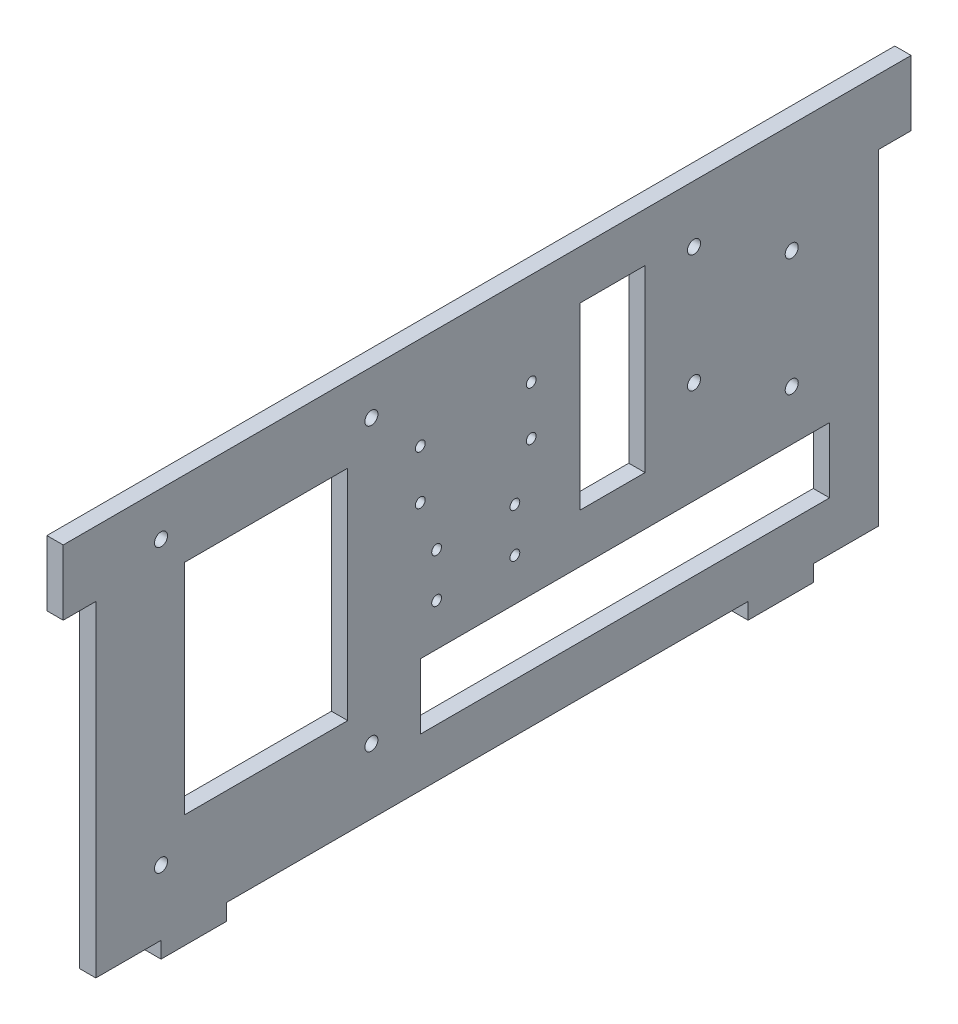
SolidWorks part; units mm, degrees
material "Perspex (TM) GS Acrylic Cast Sheet"
ref_plane "Ebene vorne" through (0, 0, 0) normal (0, 0, 1) x (1, 0, 0)
ref_plane "Ebene oben" through (0, 0, 0) normal (0, 1, 0) x (1, 0, 0)
ref_plane "Ebene rechts" through (0, 0, 0) normal (1, 0, 0) x (0, 0, -1)
sketch "Skizze2" plane through (0, 0, 0) normal (1, 0, 0) x (0, 0, -1)
  line L1 (-120, 60) -> (120, 60)
  line L2 (-120, 60) -> (-120, -60)
  line L3 (-120, -60) -> (120, -60)
  line L4 (120, 60) -> (120, -60)
  line L5 (-120, 60) -> (120, -60) construction
  line L6 (-120, -60) -> (120, 60) construction
  line L7 (-120, 60) -> (-130, 60)
  line L8 (-120, 60) -> (-120, 40)
  line L9 (-120, 40) -> (-130, 40)
  line L10 (-130, 60) -> (-130, 40)
  line L11 (-120, 60) -> (-130, 40) construction
  line L12 (-120, 40) -> (-130, 60) construction
  line L13 (120, 60) -> (130, 60)
  line L14 (120, 60) -> (120, 40)
  line L15 (120, 40) -> (130, 40)
  line L16 (130, 60) -> (130, 40)
  line L17 (120, 60) -> (130, 40) construction
  line L18 (120, 40) -> (130, 60) construction
  line L19 (100, -60) -> (80, -60)
  line L20 (100, -60) -> (100, -65)
  line L21 (100, -65) -> (80, -65)
  line L22 (80, -60) -> (80, -65)
  line L23 (-80, -60) -> (-100, -60)
  line L24 (-80, -60) -> (-80, -65)
  line L25 (-80, -65) -> (-100, -65)
  line L26 (-100, -60) -> (-100, -65)
  point P0 (0, 0)
  point P9 (-125, 50)
  point P13 (125, 50)
  dimension "D1" = 240
  dimension "D2" = 120
  dimension "D3" = 10
  dimension "D4" = 20
  dimension "D5" = 20
  dimension "D6" = 20
  dimension "D7" = 5
  dimension "D8" = 20
extrude "Aufsatz-Linear austragen1" add sketch "Skizze2" along normal blind 5
sketch "Skizze3" plane through (0, 0, 0) normal (-1, 0, 0) x (0, 0, 1)
  line L0 (80, -60) -> (-80, -60) construction
  line L1 (35.5, 46.5) -> (100, 46.5) construction
  line L2 (35.5, 46.5) -> (35.5, -40) construction
  line L3 (35.5, -40) -> (100, -40) construction
  line L4 (100, 46.5) -> (100, -40) construction
  line L5 (35.5, 46.5) -> (100, -40) construction
  line L6 (35.5, -40) -> (100, 46.5) construction
  line L7 (3.5, 24) -> (3.5, -5.25) construction
  line L8 (120, 40) -> (120, -60) construction
  line L9 (-13.5, 16.5) -> (20.5, 16.5) construction
  line L10 (-13.5, 16.5) -> (-13.5, 31.5) construction
  line L11 (-13.5, 31.5) -> (20.5, 31.5) construction
  line L12 (20.5, 16.5) -> (20.5, 31.5) construction
  line L13 (-13.5, 16.5) -> (20.5, 31.5) construction
  line L14 (-13.5, 31.5) -> (20.5, 16.5) construction
  line L15 (-8.5, -12) -> (15.5, -12) construction
  line L16 (-8.5, -12) -> (-8.5, 1.5) construction
  line L17 (-8.5, 1.5) -> (15.5, 1.5) construction
  line L18 (15.5, -12) -> (15.5, 1.5) construction
  line L19 (-8.5, -12) -> (15.5, 1.5) construction
  line L20 (-8.5, 1.5) -> (15.5, -12) construction
  circle A0 centre (35.5, 46.5) radius 2
  circle A1 centre (100, 46.5) radius 2
  circle A2 centre (100, -40) radius 2
  circle A3 centre (35.5, -40) radius 2
  circle A4 centre (20.5, 31.5) radius 1.5
  circle A5 centre (-13.5, 31.5) radius 1.5
  circle A6 centre (-13.5, 16.5) radius 1.5
  circle A7 centre (20.5, 16.5) radius 1.5
  circle A8 centre (15.5, 1.5) radius 1.5
  circle A9 centre (15.5, -12) radius 1.5
  circle A10 centre (-8.5, 1.5) radius 1.5
  circle A11 centre (-8.5, -12) radius 1.5
  point P0 (67.75, 3.25)
  point P13 (3.5, 24)
  point P22 (20.5, 24)
  point P23 (3.5, -5.25)
  dimension "D1" = 4
  dimension "D6" = 3
  dimension "D11" = 3
  dimension "D2" = 64.5
  dimension "D3" = 86.5
  dimension "D4" = 20
  dimension "D5" = 20
  dimension "D7" = 34
  dimension "D8" = 15
  dimension "D9" = 15
  dimension "D10" = 15
  dimension "D12" = 24
  dimension "D13" = 13.5
  dimension "D14" = 15
extrude "Schnitt-Linear austragen1" cut sketch "Skizze3" against normal through all
sketch "Skizze4" plane through (5, 0, 0) normal (1, 0, 0) x (0, 0, -1)
  line L0 (120, 40) -> (120, -60) construction
  line L1 (56.82, 45) -> (100, 45) construction
  line L2 (56.82, 45) -> (56.82, 23.92) construction
  line L3 (56.82, 23.92) -> (100, 23.92) construction
  line L4 (100, 45) -> (100, 23.92) construction
  line L5 (56.82, 45) -> (100, 23.92) construction
  line L6 (56.82, 23.92) -> (100, 45) construction
  line L7 (63.424, 42.46) -> (93.396, 42.46) construction
  line L8 (63.424, 42.46) -> (63.424, 26.46) construction
  line L9 (63.424, 26.46) -> (93.396, 26.46) construction
  line L10 (93.396, 42.46) -> (93.396, 26.46) construction
  line L11 (63.424, 42.46) -> (93.396, 26.46) construction
  line L12 (63.424, 26.46) -> (93.396, 42.46) construction
  line L13 (56.82, 8.92) -> (100, 8.92) construction
  line L14 (56.82, 8.92) -> (56.82, -12.16) construction
  line L15 (56.82, -12.16) -> (100, -12.16) construction
  line L16 (100, 8.92) -> (100, -12.16) construction
  line L17 (56.82, 8.92) -> (100, -12.16) construction
  line L18 (56.82, -12.16) -> (100, 8.92) construction
  line L19 (63.424, 6.38) -> (93.396, 6.38) construction
  line L20 (63.424, 6.38) -> (63.424, -9.62) construction
  line L21 (63.424, -9.62) -> (93.396, -9.62) construction
  line L22 (93.396, 6.38) -> (93.396, -9.62) construction
  line L23 (63.424, 6.38) -> (93.396, -9.62) construction
  line L24 (63.424, -9.62) -> (93.396, 6.38) construction
  line L25 (-130, 60) -> (130, 60) construction
  circle A0 centre (63.424, 42.46) radius 2
  circle A1 centre (93.396, 26.46) radius 2
  circle A2 centre (63.424, 6.38) radius 2
  circle A3 centre (93.396, -9.62) radius 2
  point P0 (78.41, 34.46)
  point P5 (78.41, 34.46)
  point P10 (63.424, 34.46)
  point P11 (56.82, 34.46)
  point P16 (78.41, -1.62)
  point P21 (78.41, -1.62)
  point P26 (63.424, -1.62)
  point P27 (56.82, -1.62)
  dimension "D5" = 4
  dimension "D11" = 4
  dimension "D1" = 2.54
  dimension "D2" = 6.604
  dimension "D3" = 21.08
  dimension "D4" = 43.18
  dimension "D6" = 20
  dimension "D7" = 2.54
  dimension "D8" = 6.604
  dimension "D9" = 21.08
  dimension "D10" = 43.18
  dimension "D12" = 15
  dimension "D13" = 15
extrude "Schnitt-Linear austragen2" cut sketch "Skizze4" against normal through all
sketch "Skizze6" plane through (5, 0, 0) normal (1, 0, 0) x (0, 0, -1)
  line L0 (-100, 46.5) -> (-35.5, -40) construction
  line L1 (-80, -60) -> (80, -60) construction
  line L2 (-92.75, 36.7771) -> (-42.75, 36.7771)
  line L3 (-92.75, 36.7771) -> (-92.75, -30.2771)
  line L4 (-92.75, -30.2771) -> (-42.75, -30.2771)
  line L5 (-42.75, 36.7771) -> (-42.75, -30.2771)
  line L6 (-92.75, 36.7771) -> (-42.75, -30.2771) construction
  line L7 (-92.75, -30.2771) -> (-42.75, 36.7771) construction
  line L8 (-20.5, -25) -> (105, -25)
  line L9 (-20.5, -25) -> (-20.5, -45)
  line L10 (-20.5, -45) -> (105, -45)
  line L11 (105, -25) -> (105, -45)
  line L12 (-20.5, -25) -> (105, -45) construction
  line L13 (-20.5, -45) -> (105, -25) construction
  line L14 (28.5, 45) -> (48.424, 45)
  line L15 (28.5, 45) -> (28.5, -10)
  line L16 (28.5, -10) -> (48.424, -10)
  line L17 (48.424, 45) -> (48.424, -10)
  line L18 (28.5, 45) -> (48.424, -10) construction
  line L19 (28.5, -10) -> (48.424, 45) construction
  line L20 (120, 40) -> (120, -60) construction
  line L21 (-130, 60) -> (130, 60) construction
  circle A0 centre (13.5, 31.5) radius 1.5 construction
  circle A1 centre (63.424, 42.46) radius 2 construction
  point P2 (-67.75, 3.25)
  point P9 (42.25, -35)
  point P14 (38.462, 17.5)
  dimension "D1" = 50
  dimension "D2" = 20
  dimension "D3" = 15
  dimension "D4" = 15
  dimension "D5" = 15
  dimension "D6" = 15
  dimension "D7" = 15
  dimension "D8" = 15
  dimension "D9" = 15
extrude "Schnitt-Linear austragen3" cut sketch "Skizze6" against normal through all
